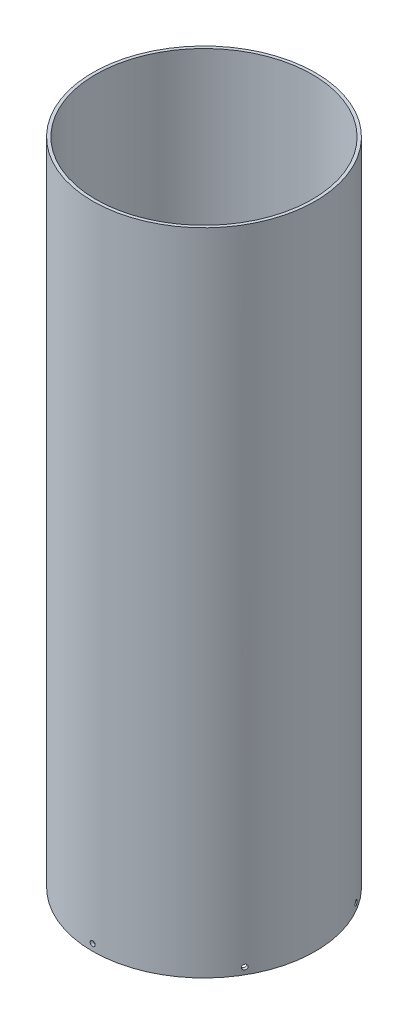
SolidWorks part; units mm, degrees
ref_plane "Front Plane" through (0, 0, 0) normal (0, 0, 1) x (1, 0, 0)
ref_plane "Top Plane" through (0, 0, 0) normal (0, 1, 0) x (1, 0, 0)
ref_plane "Right Plane" through (0, 0, 0) normal (1, 0, 0) x (0, 0, -1)
sketch "Sketch1" plane through (0, 0, 0) normal (0, 1, 0) x (1, 0, 0)
  circle A0 centre (0, 0) radius 76.2
  circle A1 centre (0, 0) radius 78.359
  dimension "D1" = 152.4
  dimension "D2" = 156.718
extrude "Boss-Extrude1" add sketch "Sketch1" along normal blind 457.2
ref_axis "Axis1" through (0, 457.2, 0) along (0, -1, 0)
sketch "Sketch2" plane through (0, 0, 0) normal (0, 0, 1) x (1, 0, 0)
  line L0 (0, 0) -> (0, 4.7625) construction
  circle A0 centre (0, 4.7625) radius 1.75
  dimension "D1" = 3.5
  dimension "D2" = 4.7625
extrude "Cut-Extrude1" cut sketch "Sketch2" against normal through all
pattern_circular "CirPattern1" count 6 over 360 about axis through (0, 457.2, 0) along (0, -1, 0) of "Cut-Extrude1"
equation "\"D1@Boss-Extrude1\"=\"Aft_Upper_Length\""
equation "\"AB_Coupling_Section_Length\"= 0.375in"
equation "\"AB_Coupler_Num_Screws\"= 6"
equation "\"AB_Coupling_Screw_Diameter\"= 3.5mm"
equation "\"AB_Coupler_OD_Length\"= 2in"
equation "\"AB_Coupler_Length\"= \"AB_Coupler_OD_Length\" + \"AB_Coupling_Section_Length\" * 2"
equation "\"D1@Sketch2\"=\"AB_Coupling_Screw_Diameter\""
equation "\"D2@Sketch2\"=\"AB_Coupling_Section_Length\"/2"
equation "\"D1@CirPattern1\"=\"AB_Coupler_Num_Screws\""
equation "\"Aft_Section_Length\"= 40in"
equation "\"Aft_Upper_Length\"= \"Aft_Section_Length\" - \"Aft_Lower_Length\" - \"AB_Coupler_OD_Length\""
equation "\"Aft_Lower_Length\"= 20in"
